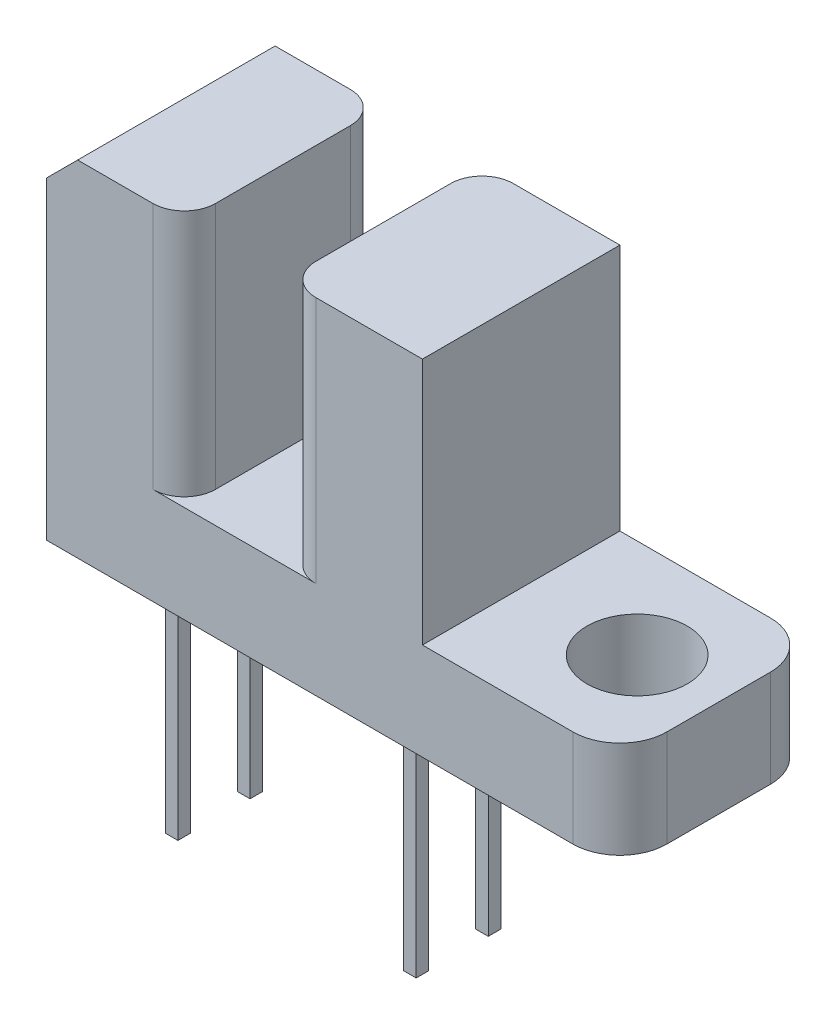
SolidWorks part; units mm, degrees
ref_plane "Front" through (0, 0, 0) normal (0, 0, 1) x (1, 0, 0)
ref_plane "Top" through (0, 0, 0) normal (0, 1, 0) x (1, 0, 0)
ref_plane "Right" through (0, 0, 0) normal (1, 0, 0) x (0, 0, -1)
sketch "Sketch1" plane through (0, 0, 0) normal (0, 1, 0) x (1, 0, 0)
  line L1 (-9.15, 3.15) -> (9.15, 3.15)
  line L2 (-9.15, 3.15) -> (-9.15, -3.15)
  line L3 (-9.15, -3.15) -> (9.15, -3.15)
  line L4 (9.15, 3.15) -> (9.15, -3.15)
  line L5 (-9.15, 3.15) -> (9.15, -3.15) construction
  line L6 (-9.15, -3.15) -> (9.15, 3.15) construction
  point P0 (0, 0)
  dimension "D1" = 18.3
  dimension "D2" = 6.3
extrude "Boss-Extrude1" add sketch "Sketch1" along normal blind 3.1
fillet "Fillet1" radius 1.5 2 edges at (9.15, 1.55, -3.15) (9.15, 1.55, 3.15)
sketch "Sketch2" plane through (0, 3.1, 0) normal (0, 1, 0) x (1, 0, 0)
  line L0 (7.65, 3.15) -> (-9.15, 3.15) construction
  line L1 (-9.15, -3.15) -> (2.85, -3.15)
  line L2 (-9.15, -3.15) -> (-9.15, 3.15)
  line L3 (-9.15, 3.15) -> (2.85, 3.15)
  line L4 (2.85, -3.15) -> (2.85, 3.15)
  dimension "D1" = 12
extrude "Boss-Extrude2" add sketch "Sketch2" along normal blind 7.9
hole_wizard "Ø3.2 (3.2) Diameter Hole1" positions "Sketch3" profile "Sketch4" hole size "Ø3.2" standard "DIN" end condition through all
sketch "Sketch3" plane through (0, 3.1, 0) normal (0, 1, 0) x (1, 0, 0)
  line L0 (9.15, -1.65) -> (9.15, 1.65) construction
  point P0 (6.55, 0)
  dimension "D1" = 2.6
sketch "Sketch4" plane through (6.55, 3.1, 0) normal (1, 0, 0) x (0, 0, 1)
  line L0 (0, 0) -> (0, 3.1)
  line L1 (0, 3.1) -> (1.6, 3.1)
  line L2 (1.6, 3.1) -> (1.6, 0)
  line L5 (1.6, 0) -> (0, 0)
  line L11 (0, -6.35) -> (0, 107.95) construction
  dimension "Thru Hole Dia." = 3.2
  dimension "Thru Hole Depth" = 3.1
sketch "Sketch5" plane through (0, 0, 3.15) normal (0, 0, 1) x (1, 0, 0)
  line L0 (-9.15, 11) -> (2.85, 11) construction
  line L1 (-4.75, 11) -> (-1.55, 11)
  line L2 (-4.75, 11) -> (-4.75, 3.1)
  line L3 (-4.75, 3.1) -> (-1.55, 3.1)
  line L4 (-1.55, 11) -> (-1.55, 3.1)
  line L5 (-9.15, 11) -> (-9.15, 0) construction
  dimension "D1" = 4.4
  dimension "D2" = 3.2
  dimension "D3" = 7.9
extrude "Cut-Extrude1" cut sketch "Sketch5" against normal through all
chamfer "Chamfer1" distance 1 angle 45 1 edges at (-9.15, 11, 0)
fillet "Fillet2" radius 1 4 edges at (-1.55, 7.05, -3.15) (-1.55, 7.05, 3.15) (-4.75, 7.05, 3.15) (-4.75, 7.05, -3.15)
sketch "Sketch6" plane through (0, 0, 0) normal (0, -1, 0) x (1, 0, 0)
  line L0 (-9.15, 3.15) -> (7.65, 3.15) construction
  line L1 (0.45, 1.35) -> (0.85, 1.35)
  line L2 (0.45, 1.35) -> (0.45, 0.95)
  line L3 (0.45, 0.95) -> (0.85, 0.95)
  line L4 (0.85, 1.35) -> (0.85, 0.95)
  line L5 (0.45, 1.35) -> (0.85, 0.95) construction
  line L6 (0.45, 0.95) -> (0.85, 1.35) construction
  line L7 (0.45, -0.95) -> (0.85, -0.95)
  line L8 (0.45, -0.95) -> (0.45, -1.35)
  line L9 (0.45, -1.35) -> (0.85, -1.35)
  line L10 (0.85, -0.95) -> (0.85, -1.35)
  line L11 (0.45, -0.95) -> (0.85, -1.35) construction
  line L12 (0.45, -1.35) -> (0.85, -0.95) construction
  line L13 (-9.15, -3.15) -> (-9.15, 3.15) construction
  point P0 (0.65, 1.15)
  point P5 (0.65, -1.15)
  dimension "D1" = 0.4
  dimension "D2" = 0.4
  dimension "D3" = 0.4
  dimension "D4" = 0.4
  dimension "D5" = 2.7
  dimension "D6" = 1.8
  dimension "D7" = 10
  dimension "D8" = 0
extrude "Boss-Extrude3" add sketch "Sketch6" along normal blind 8
pattern_linear "LPattern1" count 2 spacing 7.6 along (-1, 0, 0) of "Boss-Extrude3"
